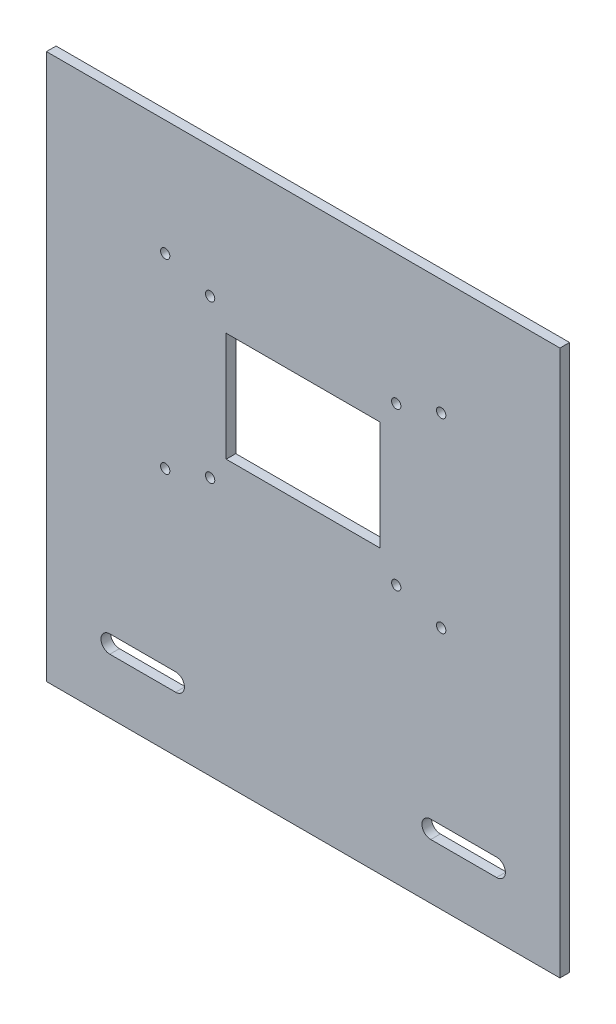
SolidWorks part; units mm, degrees
ref_plane "前视基准面" through (0, 0, 0) normal (0, 0, 1) x (1, 0, 0)
ref_plane "上视基准面" through (0, 0, 0) normal (0, 1, 0) x (1, 0, 0)
ref_plane "右视基准面" through (0, 0, 0) normal (1, 0, 0) x (0, 0, -1)
other "Configuration Table"
sketch "外形与孔位_compute_combo_plate" plane through (0, 0, 0) normal (0, 0, 1) x (1, 0, 0)
  line L0 (0, 0) -> (160, 0)
  line L1 (160, 0) -> (160, 170)
  line L2 (160, 170) -> (0, 170)
  line L3 (0, 170) -> (0, 0)
  line L4 (56, 88) -> (104, 88)
  line L5 (104, 88) -> (104, 122)
  line L6 (104, 122) -> (56, 122)
  line L7 (56, 122) -> (56, 88)
  line L8 (19.75, 22.75) -> (40.25, 22.75)
  line L9 (40.25, 17.25) -> (19.75, 17.25)
  line L10 (119.75, 22.75) -> (140.25, 22.75)
  line L11 (140.25, 17.25) -> (119.75, 17.25)
  circle A0 centre (51, 80.5) radius 1.45
  circle A1 centre (51, 129.5) radius 1.45
  circle A2 centre (109, 80.5) radius 1.45
  circle A3 centre (109, 129.5) radius 1.45
  circle A4 centre (37, 76) radius 1.45
  circle A5 centre (37, 134) radius 1.45
  circle A6 centre (123, 76) radius 1.45
  circle A7 centre (123, 134) radius 1.45
  arc A8 (40.25, 22.75) -> (40.25, 17.25) centre (40.25, 20) cw
  arc A9 (19.75, 17.25) -> (19.75, 22.75) centre (19.75, 20) cw
  arc A10 (140.25, 22.75) -> (140.25, 17.25) centre (140.25, 20) cw
  arc A11 (119.75, 17.25) -> (119.75, 22.75) centre (119.75, 20) cw
extrude "板厚_3mm" add sketch "外形与孔位_compute_combo_plate" along normal blind 3
